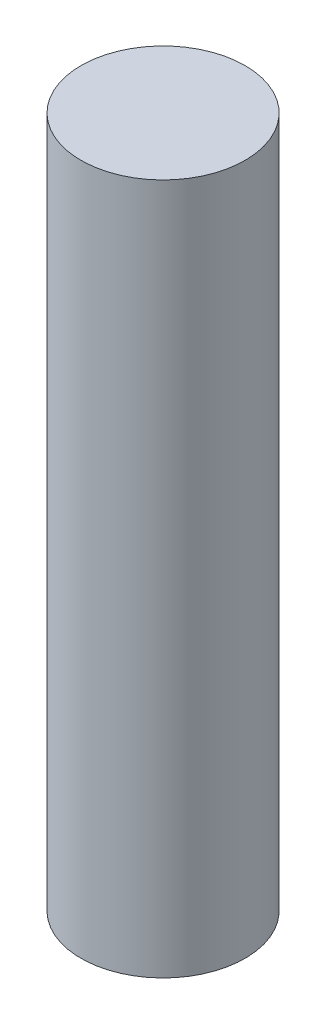
SolidWorks part; units mm, degrees
material "Cast Alloy Steel"
ref_plane "Front Plane" through (0, 0, 0) normal (0, 0, 1) x (1, 0, 0)
ref_plane "Top Plane" through (0, 0, 0) normal (0, 1, 0) x (1, 0, 0)
ref_plane "Right Plane" through (0, 0, 0) normal (1, 0, 0) x (0, 0, -1)
sketch "Sketch1" plane through (0, 0, 0) normal (0, 1, 0) x (1, 0, 0)
  circle A0 centre (0, 0) radius 47.5089
extrude "Boss-Extrude1" add sketch "Sketch1" along normal blind 400 contours A0
